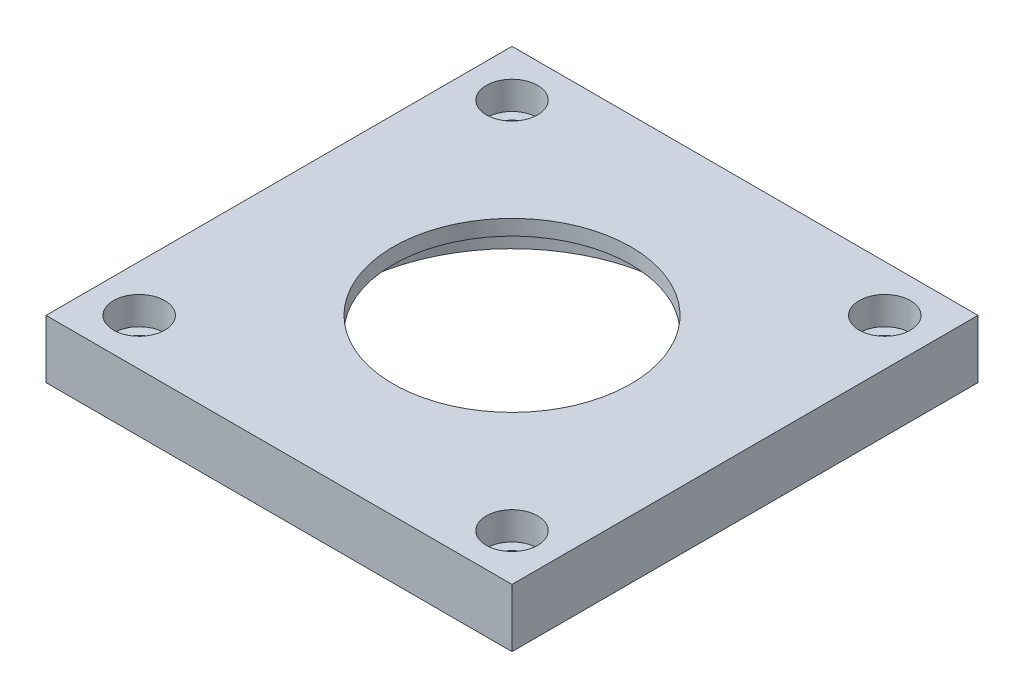
SolidWorks part; units mm, degrees
ref_plane "Alzado" through (0, 0, 0) normal (0, 0, 1) x (1, 0, 0)
ref_plane "Planta" through (0, 0, 0) normal (0, 1, 0) x (1, 0, 0)
ref_plane "Vista lateral" through (0, 0, 0) normal (1, 0, 0) x (0, 0, -1)
sketch "Croquis1" plane through (0, 0, 0) normal (0, 1, 0) x (1, 0, 0)
  line L1 (-50, 50) -> (50, 50)
  line L2 (-50, 50) -> (-50, -50)
  line L3 (-50, -50) -> (50, -50)
  line L4 (50, 50) -> (50, -50)
  line L5 (-50, 50) -> (50, -50) construction
  line L6 (-50, -50) -> (50, 50) construction
  point P0 (0, 0)
  dimension "D2" = 100
extrude "Saliente-Extruir1" add sketch "Croquis1" along normal blind 12.5
sketch "Croquis3" plane through (0, 0, 0) normal (0, -1, 0) x (1, 0, 0)
  circle A0 centre (0, 0) radius 35.2
  dimension "D1" = 70.4
extrude "Cortar-Extruir1" cut sketch "Croquis3" against normal blind 9.2
sketch "Croquis4" plane through (0, 9.2, 0) normal (0, -1, 0) x (1, 0, 0)
  circle A0 centre (0, 0) radius 25.5
  dimension "D1" = 51
extrude "Cortar-Extruir2" cut sketch "Croquis4" against normal through all
sketch "Croquis5" plane through (0, 0, 0) normal (0, -1, 0) x (1, 0, 0)
  line L1 (-40, 40) -> (40, 40) construction
  line L2 (-40, 40) -> (-40, -40) construction
  line L3 (-40, -40) -> (40, -40) construction
  line L4 (40, 40) -> (40, -40) construction
  line L5 (-40, 40) -> (40, -40) construction
  line L6 (-40, -40) -> (40, 40) construction
  circle A0 centre (-40, 40) radius 3.25
  point P0 (0, 0)
  dimension "D3" = 6.5
  dimension "D1" = 80
extrude "Cortar-Extruir3" cut sketch "Croquis5" against normal through all
pattern_circular "MatrizC1" count 4 over 360 about axis through (0, 0, 0) along (0, 1, 0) of "Cortar-Extruir3"
sketch "Croquis6" plane through (0, 12.5, 0) normal (0, 1, 0) x (1, 0, 0)
  circle A21 centre (-40, 40) radius 5.5
  dimension "D1" = 11
extrude "Cortar-Extruir4" cut sketch "Croquis6" against normal blind 6
pattern_circular "MatrizC2" count 4 over 360 about axis through (0, 0, 0) along (0, 1, 0) of "Cortar-Extruir4"
